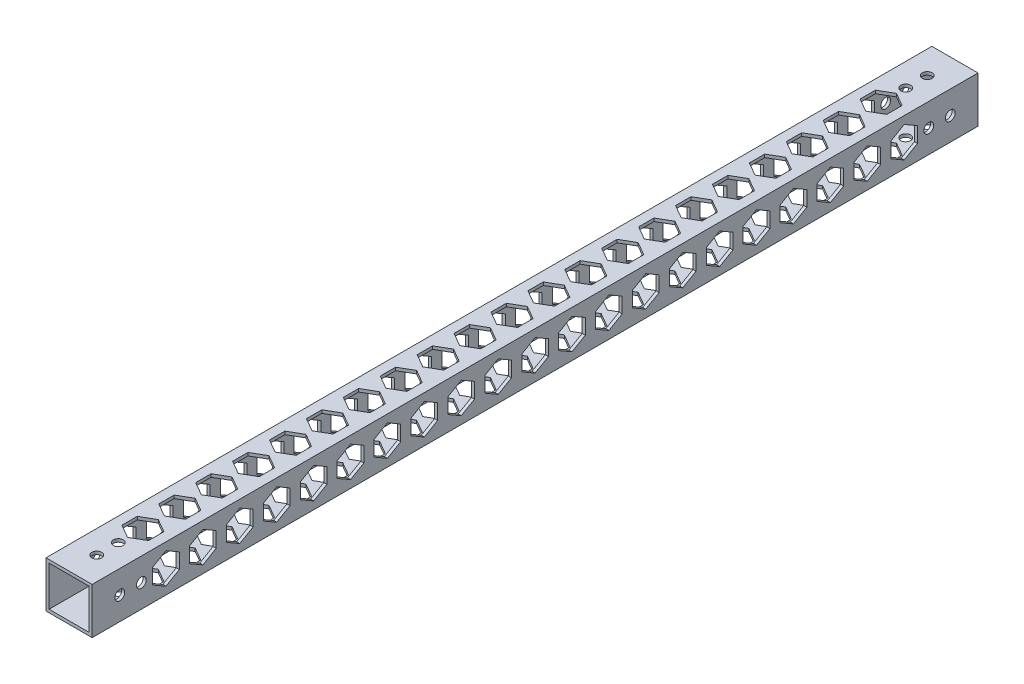
SolidWorks part; units mm, degrees
ref_plane "前视基准面" through (0, 0, 0) normal (0, 0, 1) x (1, 0, 0)
ref_plane "上视基准面" through (0, 0, 0) normal (0, 1, 0) x (1, 0, 0)
ref_plane "右视基准面" through (0, 0, 0) normal (1, 0, 0) x (0, 0, -1)
other "Configuration Table"
sketch "草图1" plane through (0, 0, 0) normal (0, 0, 1) x (1, 0, 0)
  line L1 (6.5, -6.5) -> (-6.5, -6.5)
  line L2 (6.5, -6.5) -> (6.5, 6.5)
  line L3 (6.5, 6.5) -> (-6.5, 6.5)
  line L4 (-6.5, -6.5) -> (-6.5, 6.5)
  line L5 (6.5, -6.5) -> (-6.5, 6.5) construction
  line L6 (6.5, 6.5) -> (-6.5, -6.5) construction
  line L7 (7.5, -7.5) -> (-7.5, -7.5)
  line L8 (7.5, -7.5) -> (7.5, 7.5)
  line L9 (7.5, 7.5) -> (-7.5, 7.5)
  line L10 (-7.5, -7.5) -> (-7.5, 7.5)
  line L11 (7.5, -7.5) -> (-7.5, 7.5) construction
  line L12 (7.5, 7.5) -> (-7.5, -7.5) construction
  point P0 (0, 0)
  point P6 (0, 0)
  dimension "D1" = 15
  dimension "D2" = 13
extrude "凸台-拉伸1" add sketch "草图1" along normal blind 288
sketch "草图2" plane through (0, 7.5, 0) normal (0, 1, 0) x (1, 0, 0)
  line L0 (-7.5, -4) -> (7.5, -4) construction
  line L1 (-7.5, -288) -> (-7.5, 0) construction
  line L2 (7.5, -288) -> (7.5, 0) construction
  line L3 (7.5, 0) -> (-7.5, 0) construction
  line L4 (0, 0) -> (0, -9) construction
  line L5 (-7.5, -144) -> (7.5, -144) construction
  line L6 (-7.5, -284) -> (7.5, -284) construction
  line L7 (0, -151) -> (-4.3301, -153.5)
  line L8 (0, -139) -> (-4.3301, -141.5)
  line L9 (-4.3301, -141.5) -> (-4.3301, -146.5)
  line L10 (-4.3301, -146.5) -> (0, -149)
  line L11 (0, -149) -> (4.3301, -146.5)
  line L12 (4.3301, -146.5) -> (4.3301, -141.5)
  line L13 (4.3301, -141.5) -> (0, -139)
  line L14 (-4.3301, -153.5) -> (-4.3301, -158.5)
  line L15 (-4.3301, -158.5) -> (0, -161)
  line L16 (0, -161) -> (4.3301, -158.5)
  line L17 (4.3301, -158.5) -> (4.3301, -153.5)
  line L18 (4.3301, -153.5) -> (0, -151)
  line L19 (0, -163) -> (-4.3301, -165.5)
  line L20 (-4.3301, -165.5) -> (-4.3301, -170.5)
  line L21 (-4.3301, -170.5) -> (0, -173)
  line L22 (0, -173) -> (4.3301, -170.5)
  line L23 (4.3301, -170.5) -> (4.3301, -165.5)
  line L24 (4.3301, -165.5) -> (0, -163)
  line L25 (0, -175) -> (-4.3301, -177.5)
  line L26 (-4.3301, -177.5) -> (-4.3301, -182.5)
  line L27 (-4.3301, -182.5) -> (0, -185)
  line L28 (0, -185) -> (4.3301, -182.5)
  line L29 (4.3301, -182.5) -> (4.3301, -177.5)
  line L30 (4.3301, -177.5) -> (0, -175)
  line L31 (0, -187) -> (-4.3301, -189.5)
  line L32 (-4.3301, -189.5) -> (-4.3301, -194.5)
  line L33 (-4.3301, -194.5) -> (0, -197)
  line L34 (0, -197) -> (4.3301, -194.5)
  line L35 (4.3301, -194.5) -> (4.3301, -189.5)
  line L36 (4.3301, -189.5) -> (0, -187)
  line L37 (0, -199) -> (-4.3301, -201.5)
  line L38 (-4.3301, -201.5) -> (-4.3301, -206.5)
  line L39 (-4.3301, -206.5) -> (0, -209)
  line L40 (0, -209) -> (4.3301, -206.5)
  line L41 (4.3301, -206.5) -> (4.3301, -201.5)
  line L42 (4.3301, -201.5) -> (0, -199)
  line L43 (0, -211) -> (-4.3301, -213.5)
  line L44 (-4.3301, -213.5) -> (-4.3301, -218.5)
  line L45 (-4.3301, -218.5) -> (0, -221)
  line L46 (0, -221) -> (4.3301, -218.5)
  line L47 (4.3301, -218.5) -> (4.3301, -213.5)
  line L48 (4.3301, -213.5) -> (0, -211)
  line L49 (0, -223) -> (-4.3301, -225.5)
  line L50 (-4.3301, -225.5) -> (-4.3301, -230.5)
  line L51 (-4.3301, -230.5) -> (0, -233)
  line L52 (0, -233) -> (4.3301, -230.5)
  line L53 (4.3301, -230.5) -> (4.3301, -225.5)
  line L54 (4.3301, -225.5) -> (0, -223)
  line L55 (0, -235) -> (-4.3301, -237.5)
  line L56 (-4.3301, -237.5) -> (-4.3301, -242.5)
  line L57 (-4.3301, -242.5) -> (0, -245)
  line L58 (0, -245) -> (4.3301, -242.5)
  line L59 (4.3301, -242.5) -> (4.3301, -237.5)
  line L60 (4.3301, -237.5) -> (0, -235)
  line L61 (0, -247) -> (-4.3301, -249.5)
  line L62 (-4.3301, -249.5) -> (-4.3301, -254.5)
  line L63 (-4.3301, -254.5) -> (0, -257)
  line L64 (0, -257) -> (4.3301, -254.5)
  line L65 (4.3301, -254.5) -> (4.3301, -249.5)
  line L66 (4.3301, -249.5) -> (0, -247)
  line L67 (0, -259) -> (-4.3301, -261.5)
  line L68 (-4.3301, -261.5) -> (-4.3301, -266.5)
  line L69 (-4.3301, -266.5) -> (0, -269)
  line L70 (0, -269) -> (4.3301, -266.5)
  line L71 (4.3301, -266.5) -> (4.3301, -261.5)
  line L72 (4.3301, -261.5) -> (0, -259)
  line L73 (0, -127) -> (-4.3301, -129.5)
  line L74 (-4.3301, -129.5) -> (-4.3301, -134.5)
  line L75 (-4.3301, -134.5) -> (0, -137)
  line L76 (0, -137) -> (4.3301, -134.5)
  line L77 (4.3301, -134.5) -> (4.3301, -129.5)
  line L78 (4.3301, -129.5) -> (0, -127)
  line L79 (0, -115) -> (-4.3301, -117.5)
  line L80 (-4.3301, -117.5) -> (-4.3301, -122.5)
  line L81 (-4.3301, -122.5) -> (0, -125)
  line L82 (0, -125) -> (4.3301, -122.5)
  line L83 (4.3301, -122.5) -> (4.3301, -117.5)
  line L84 (4.3301, -117.5) -> (0, -115)
  line L85 (0, -103) -> (-4.3301, -105.5)
  line L86 (-4.3301, -105.5) -> (-4.3301, -110.5)
  line L87 (-4.3301, -110.5) -> (0, -113)
  line L88 (0, -113) -> (4.3301, -110.5)
  line L89 (4.3301, -110.5) -> (4.3301, -105.5)
  line L90 (4.3301, -105.5) -> (0, -103)
  line L91 (0, -91) -> (-4.3301, -93.5)
  line L92 (-4.3301, -93.5) -> (-4.3301, -98.5)
  line L93 (-4.3301, -98.5) -> (0, -101)
  line L94 (0, -101) -> (4.3301, -98.5)
  line L95 (4.3301, -98.5) -> (4.3301, -93.5)
  line L96 (4.3301, -93.5) -> (0, -91)
  line L97 (0, -79) -> (-4.3301, -81.5)
  line L98 (-4.3301, -81.5) -> (-4.3301, -86.5)
  line L99 (-4.3301, -86.5) -> (0, -89)
  line L100 (0, -89) -> (4.3301, -86.5)
  line L101 (4.3301, -86.5) -> (4.3301, -81.5)
  line L102 (4.3301, -81.5) -> (0, -79)
  line L103 (0, -67) -> (-4.3301, -69.5)
  line L104 (-4.3301, -69.5) -> (-4.3301, -74.5)
  line L105 (-4.3301, -74.5) -> (0, -77)
  line L106 (0, -77) -> (4.3301, -74.5)
  line L107 (4.3301, -74.5) -> (4.3301, -69.5)
  line L108 (4.3301, -69.5) -> (0, -67)
  line L109 (0, -55) -> (-4.3301, -57.5)
  line L110 (-4.3301, -57.5) -> (-4.3301, -62.5)
  line L111 (-4.3301, -62.5) -> (0, -65)
  line L112 (0, -65) -> (4.3301, -62.5)
  line L113 (4.3301, -62.5) -> (4.3301, -57.5)
  line L114 (4.3301, -57.5) -> (0, -55)
  line L115 (0, -43) -> (-4.3301, -45.5)
  line L116 (-4.3301, -45.5) -> (-4.3301, -50.5)
  line L117 (-4.3301, -50.5) -> (0, -53)
  line L118 (0, -53) -> (4.3301, -50.5)
  line L119 (4.3301, -50.5) -> (4.3301, -45.5)
  line L120 (4.3301, -45.5) -> (0, -43)
  line L121 (0, -31) -> (-4.3301, -33.5)
  line L122 (-4.3301, -33.5) -> (-4.3301, -38.5)
  line L123 (-4.3301, -38.5) -> (0, -41)
  line L124 (0, -41) -> (4.3301, -38.5)
  line L125 (4.3301, -38.5) -> (4.3301, -33.5)
  line L126 (4.3301, -33.5) -> (0, -31)
  line L127 (0, -19) -> (-4.3301, -21.5)
  line L128 (-4.3301, -21.5) -> (-4.3301, -26.5)
  line L129 (-4.3301, -26.5) -> (0, -29)
  line L130 (0, -29) -> (4.3301, -26.5)
  line L131 (4.3301, -26.5) -> (4.3301, -21.5)
  line L132 (4.3301, -21.5) -> (0, -19)
  circle A0 centre (0, -9) radius 1.6
  circle A2 centre (0, -279) radius 1.6
  circle A3 centre (0, -144) radius 4.3301 construction
  circle A4 centre (0, -16) radius 1.6
  circle A5 centre (0, -272) radius 1.6
  dimension "D3" = 3.2
  dimension "D1" = 4
  dimension "D2" = 5
  dimension "D4" = 5
  dimension "D8" = 7
  dimension "D5" = 11
  dimension "D6" = 11
  dimension "D7" = 2
extrude "切除-拉伸1" cut sketch "草图2" against normal up to surface (15 mm away) up to face at (0, -7.5, 144)
sketch "草图3" plane through (-7.5, 0, 0) normal (-1, 0, 0) x (0, 0, 1)
  line L0 (4, 7.5) -> (4, -7.5) construction
  line L1 (288, 7.5) -> (0, 7.5) construction
  line L2 (288, -7.5) -> (0, -7.5) construction
  line L3 (0, 7.5) -> (0, -7.5) construction
  line L4 (0, 0) -> (13.9246, 0) construction
  line L5 (144, 7.5) -> (144, -7.5) construction
  line L6 (284, 7.5) -> (284, -7.5) construction
  line L7 (156, 5) -> (151.6699, 2.5)
  line L8 (144, 5) -> (139.6699, 2.5)
  line L9 (139.6699, 2.5) -> (139.6699, -2.5)
  line L10 (139.6699, -2.5) -> (144, -5)
  line L11 (144, -5) -> (148.3301, -2.5)
  line L12 (148.3301, -2.5) -> (148.3301, 2.5)
  line L13 (148.3301, 2.5) -> (144, 5)
  line L14 (151.6699, 2.5) -> (151.6699, -2.5)
  line L15 (151.6699, -2.5) -> (156, -5)
  line L16 (156, -5) -> (160.3301, -2.5)
  line L17 (160.3301, -2.5) -> (160.3301, 2.5)
  line L18 (160.3301, 2.5) -> (156, 5)
  line L19 (168, 5) -> (163.6699, 2.5)
  line L20 (163.6699, 2.5) -> (163.6699, -2.5)
  line L21 (163.6699, -2.5) -> (168, -5)
  line L22 (168, -5) -> (172.3301, -2.5)
  line L23 (172.3301, -2.5) -> (172.3301, 2.5)
  line L24 (172.3301, 2.5) -> (168, 5)
  line L25 (180, 5) -> (175.6699, 2.5)
  line L26 (175.6699, 2.5) -> (175.6699, -2.5)
  line L27 (175.6699, -2.5) -> (180, -5)
  line L28 (180, -5) -> (184.3301, -2.5)
  line L29 (184.3301, -2.5) -> (184.3301, 2.5)
  line L30 (184.3301, 2.5) -> (180, 5)
  line L31 (192, 5) -> (187.6699, 2.5)
  line L32 (187.6699, 2.5) -> (187.6699, -2.5)
  line L33 (187.6699, -2.5) -> (192, -5)
  line L34 (192, -5) -> (196.3301, -2.5)
  line L35 (196.3301, -2.5) -> (196.3301, 2.5)
  line L36 (196.3301, 2.5) -> (192, 5)
  line L37 (204, 5) -> (199.6699, 2.5)
  line L38 (199.6699, 2.5) -> (199.6699, -2.5)
  line L39 (199.6699, -2.5) -> (204, -5)
  line L40 (204, -5) -> (208.3301, -2.5)
  line L41 (208.3301, -2.5) -> (208.3301, 2.5)
  line L42 (208.3301, 2.5) -> (204, 5)
  line L43 (216, 5) -> (211.6699, 2.5)
  line L44 (211.6699, 2.5) -> (211.6699, -2.5)
  line L45 (211.6699, -2.5) -> (216, -5)
  line L46 (216, -5) -> (220.3301, -2.5)
  line L47 (220.3301, -2.5) -> (220.3301, 2.5)
  line L48 (220.3301, 2.5) -> (216, 5)
  line L49 (228, 5) -> (223.6699, 2.5)
  line L50 (223.6699, 2.5) -> (223.6699, -2.5)
  line L51 (223.6699, -2.5) -> (228, -5)
  line L52 (228, -5) -> (232.3301, -2.5)
  line L53 (232.3301, -2.5) -> (232.3301, 2.5)
  line L54 (232.3301, 2.5) -> (228, 5)
  line L55 (240, 5) -> (235.6699, 2.5)
  line L56 (235.6699, 2.5) -> (235.6699, -2.5)
  line L57 (235.6699, -2.5) -> (240, -5)
  line L58 (240, -5) -> (244.3301, -2.5)
  line L59 (244.3301, -2.5) -> (244.3301, 2.5)
  line L60 (244.3301, 2.5) -> (240, 5)
  line L61 (252, 5) -> (247.6699, 2.5)
  line L62 (247.6699, 2.5) -> (247.6699, -2.5)
  line L63 (247.6699, -2.5) -> (252, -5)
  line L64 (252, -5) -> (256.3301, -2.5)
  line L65 (256.3301, -2.5) -> (256.3301, 2.5)
  line L66 (256.3301, 2.5) -> (252, 5)
  line L67 (264, 5) -> (259.6699, 2.5)
  line L68 (259.6699, 2.5) -> (259.6699, -2.5)
  line L69 (259.6699, -2.5) -> (264, -5)
  line L70 (264, -5) -> (268.3301, -2.5)
  line L71 (268.3301, -2.5) -> (268.3301, 2.5)
  line L72 (268.3301, 2.5) -> (264, 5)
  line L73 (132, 5) -> (127.6699, 2.5)
  line L74 (127.6699, 2.5) -> (127.6699, -2.5)
  line L75 (127.6699, -2.5) -> (132, -5)
  line L76 (132, -5) -> (136.3301, -2.5)
  line L77 (136.3301, -2.5) -> (136.3301, 2.5)
  line L78 (136.3301, 2.5) -> (132, 5)
  line L79 (120, 5) -> (115.6699, 2.5)
  line L80 (115.6699, 2.5) -> (115.6699, -2.5)
  line L81 (115.6699, -2.5) -> (120, -5)
  line L82 (120, -5) -> (124.3301, -2.5)
  line L83 (124.3301, -2.5) -> (124.3301, 2.5)
  line L84 (124.3301, 2.5) -> (120, 5)
  line L85 (108, 5) -> (103.6699, 2.5)
  line L86 (103.6699, 2.5) -> (103.6699, -2.5)
  line L87 (103.6699, -2.5) -> (108, -5)
  line L88 (108, -5) -> (112.3301, -2.5)
  line L89 (112.3301, -2.5) -> (112.3301, 2.5)
  line L90 (112.3301, 2.5) -> (108, 5)
  line L91 (96, 5) -> (91.6699, 2.5)
  line L92 (91.6699, 2.5) -> (91.6699, -2.5)
  line L93 (91.6699, -2.5) -> (96, -5)
  line L94 (96, -5) -> (100.3301, -2.5)
  line L95 (100.3301, -2.5) -> (100.3301, 2.5)
  line L96 (100.3301, 2.5) -> (96, 5)
  line L97 (84, 5) -> (79.6699, 2.5)
  line L98 (79.6699, 2.5) -> (79.6699, -2.5)
  line L99 (79.6699, -2.5) -> (84, -5)
  line L100 (84, -5) -> (88.3301, -2.5)
  line L101 (88.3301, -2.5) -> (88.3301, 2.5)
  line L102 (88.3301, 2.5) -> (84, 5)
  line L103 (72, 5) -> (67.6699, 2.5)
  line L104 (67.6699, 2.5) -> (67.6699, -2.5)
  line L105 (67.6699, -2.5) -> (72, -5)
  line L106 (72, -5) -> (76.3301, -2.5)
  line L107 (76.3301, -2.5) -> (76.3301, 2.5)
  line L108 (76.3301, 2.5) -> (72, 5)
  line L109 (60, 5) -> (55.6699, 2.5)
  line L110 (55.6699, 2.5) -> (55.6699, -2.5)
  line L111 (55.6699, -2.5) -> (60, -5)
  line L112 (60, -5) -> (64.3301, -2.5)
  line L113 (64.3301, -2.5) -> (64.3301, 2.5)
  line L114 (64.3301, 2.5) -> (60, 5)
  line L115 (48, 5) -> (43.6699, 2.5)
  line L116 (43.6699, 2.5) -> (43.6699, -2.5)
  line L117 (43.6699, -2.5) -> (48, -5)
  line L118 (48, -5) -> (52.3301, -2.5)
  line L119 (52.3301, -2.5) -> (52.3301, 2.5)
  line L120 (52.3301, 2.5) -> (48, 5)
  line L121 (36, 5) -> (31.6699, 2.5)
  line L122 (31.6699, 2.5) -> (31.6699, -2.5)
  line L123 (31.6699, -2.5) -> (36, -5)
  line L124 (36, -5) -> (40.3301, -2.5)
  line L125 (40.3301, -2.5) -> (40.3301, 2.5)
  line L126 (40.3301, 2.5) -> (36, 5)
  line L127 (24, 5) -> (19.6699, 2.5)
  line L128 (19.6699, 2.5) -> (19.6699, -2.5)
  line L129 (19.6699, -2.5) -> (24, -5)
  line L130 (24, -5) -> (28.3301, -2.5)
  line L131 (28.3301, -2.5) -> (28.3301, 2.5)
  line L132 (28.3301, 2.5) -> (24, 5)
  circle A0 centre (9, 0) radius 1.6
  circle A2 centre (279, 0) radius 1.6
  circle A3 centre (144, 0) radius 4.3301 construction
  circle A4 centre (272, 0) radius 1.6
  circle A5 centre (16, 0) radius 1.6
  dimension "D3" = 3.2
  dimension "D1" = 4
  dimension "D2" = 5
  dimension "D4" = 5
  dimension "D5" = 0
  dimension "D9" = 7
  dimension "D6" = 11
  dimension "D7" = 11
  dimension "D8" = 2
extrude "切除-拉伸2" cut sketch "草图3" against normal up to surface (15 mm away) up to face at (7.5, 0, 144)
